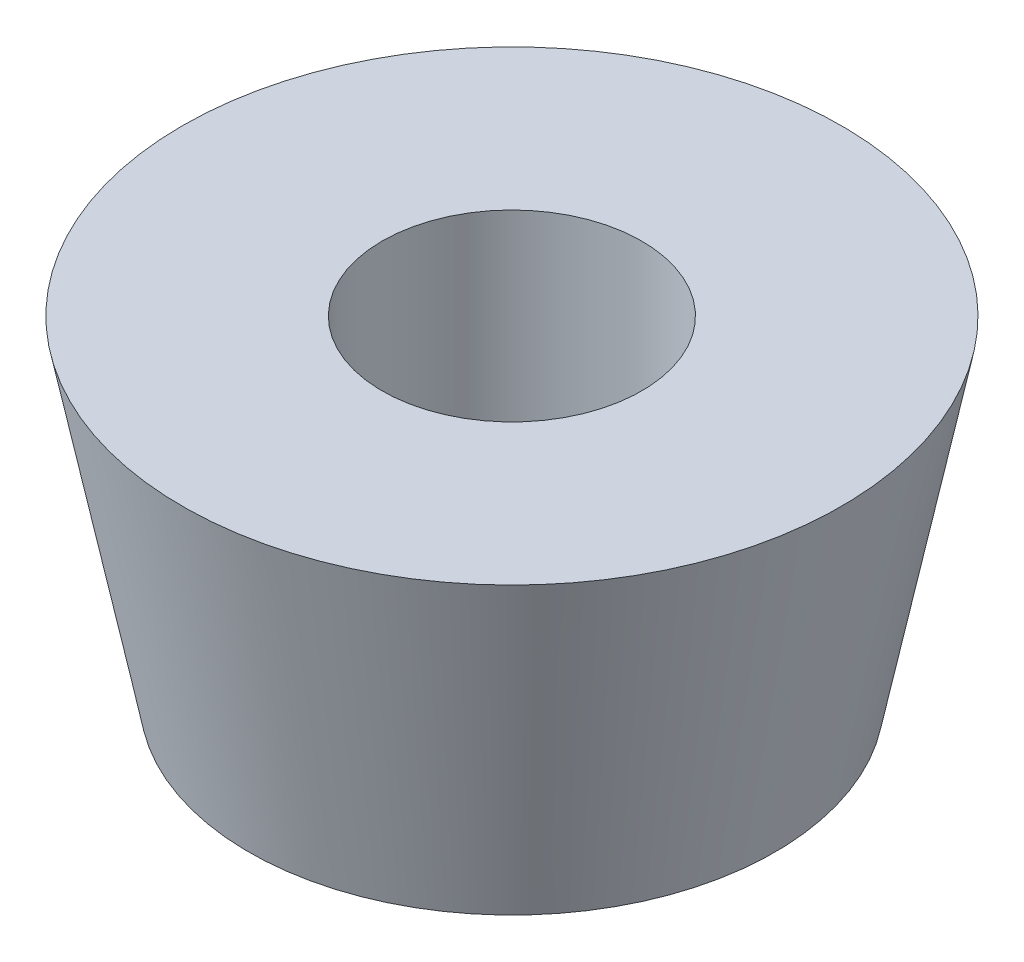
SolidWorks part; units mm, degrees
ref_plane "Front Plane" through (0, 0, 0) normal (0, 0, 1) x (1, 0, 0)
ref_plane "Top Plane" through (0, 0, 0) normal (0, 1, 0) x (1, 0, 0)
ref_plane "Right Plane" through (0, 0, 0) normal (1, 0, 0) x (0, 0, -1)
sketch "Sketch1" plane through (0, 0, 0) normal (0, 0, 1) x (1, 0, 0)
  line L0 (0, 0) -> (0, -5) construction
  line L1 (1.95, 0) -> (1.95, -5)
  line L2 (1.95, -5) -> (3.95, -5)
  line L3 (3.95, -5) -> (4.95, 0)
  line L4 (4.95, 0) -> (1.95, 0)
  point P5 (0, 0)
  dimension "D1" = 3.9
  dimension "D2" = 3
  dimension "D3" = 5
  dimension "D4" = 2
revolve "Revolve1" add sketch "Sketch1" angle 360 about L0
